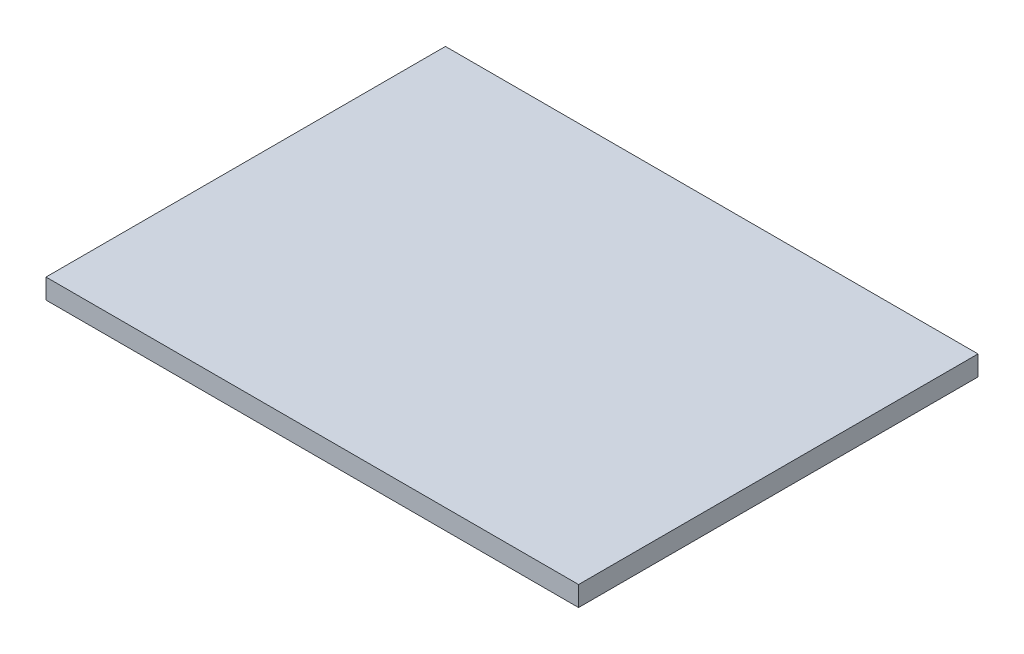
SolidWorks part; units mm, degrees
ref_plane "前视基准面" through (0, 0, 0) normal (0, 0, 1) x (1, 0, 0)
ref_plane "上视基准面" through (0, 0, 0) normal (0, 1, 0) x (1, 0, 0)
ref_plane "右视基准面" through (0, 0, 0) normal (1, 0, 0) x (0, 0, -1)
sketch "草图1" plane through (0, 0, 0) normal (0, 1, 0) x (1, 0, 0)
  line L1 (-40, 30) -> (40, 30)
  line L2 (-40, 30) -> (-40, -30)
  line L3 (-40, -30) -> (40, -30)
  line L4 (40, 30) -> (40, -30)
  line L5 (-40, 30) -> (40, -30) construction
  line L6 (-40, -30) -> (40, 30) construction
  point P0 (0, 0)
  dimension "D1" = 80
  dimension "D2" = 60
extrude "凸台-拉伸1" add sketch "草图1" along normal blind 3
